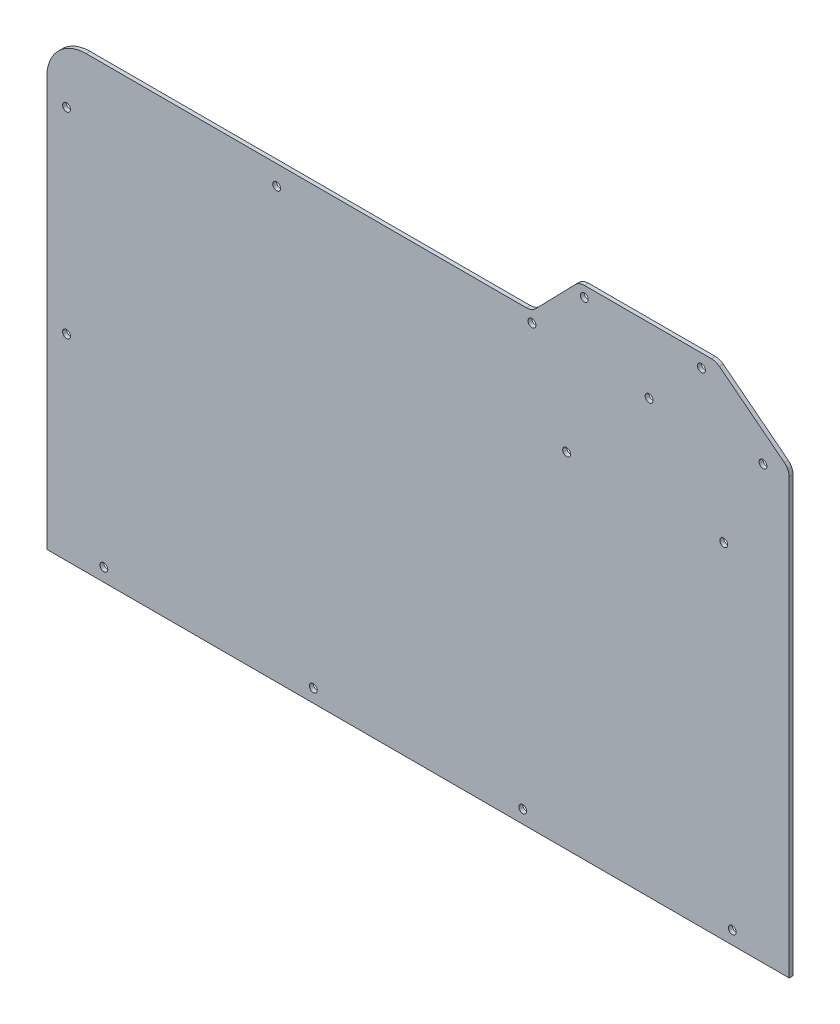
SolidWorks part; units mm, degrees
material "Alliage 1060"
ref_plane "Plan de face" through (0, 0, 0) normal (0, 0, 1) x (1, 0, 0)
ref_plane "Plan de dessus" through (0, 0, 0) normal (0, 1, 0) x (1, 0, 0)
ref_plane "Plan de droite" through (0, 0, 0) normal (1, 0, 0) x (0, 0, -1)
sketch "Esquisse1" plane through (0, 0, 0) normal (0, 0, 1) x (1, 0, 0)
  line L0 (185.25, 171.5) -> (203.25, 190)
  line L1 (0, 0) -> (283.5, 0)
  line L2 (0, 0) -> (0, 171.5)
  line L3 (0, 171.5) -> (185.25, 171.5)
  line L4 (283.5, 0) -> (283.5, 168.124)
  line L5 (203.25, 190) -> (255.5, 190)
  line L6 (255.5, 190) -> (283.5, 168.124)
  line L7 (15, 171.5) -> (180, 171.5) construction
  line L8 (201.7777, 188.4868) -> (186.7223, 173.0132) construction
  line L9 (253.7784, 190) -> (208.5, 190) construction
  line L10 (281.5783, 169.6254) -> (256.8567, 188.9401) construction
  line L11 (283.5, 165) -> (283.5, 0) construction
extrude "Boss.-Extru.1" add sketch "Esquisse1" along normal blind 1.5
sketch "Esquisse2" plane through (0, 0, 1.5) normal (0, 0, 1) x (1, 0, 0)
  circle A0 centre (261.75, 5) radius 1.5
  circle A1 centre (181.75, 5) radius 1.5
  circle A2 centre (101.75, 5) radius 1.5
  circle A3 centre (21.75, 5) radius 1.5
  circle A4 centre (7.5, 75) radius 1.5
  circle A5 centre (7.5, 150) radius 1.5
  circle A6 centre (87.75, 164) radius 1.5
  circle A7 centre (185.25, 167.5) radius 1.5
  circle A8 centre (205.25, 186) radius 1.5
  circle A9 centre (230, 165) radius 1.5
  circle A10 centre (250, 185) radius 1.5
  circle A11 centre (273.5, 165) radius 1.5
  circle A12 centre (261.75, 5) radius 1.2 construction
  circle A13 centre (181.75, 5) radius 1.2 construction
  circle A14 centre (101.75, 5) radius 1.2 construction
  circle A15 centre (21.75, 5) radius 1.2 construction
  circle A16 centre (7.5, 75) radius 1.2 construction
  circle A17 centre (7.5, 150) radius 1.2 construction
  circle A18 centre (87.75, 164) radius 1.2 construction
  circle A19 centre (185.25, 167.5) radius 1.2 construction
  circle A20 centre (205.25, 186) radius 1.2 construction
  circle A21 centre (230, 165) radius 1.25 construction
  circle A22 centre (250, 185) radius 1.25 construction
  circle A23 centre (273.5, 165) radius 1.2 construction
  dimension "D1" = 3
extrude "Enlèv. mat.-Extru.1" cut sketch "Esquisse2" against normal through all
fillet "Congé1" radius 5 4 edges at (283.5, 168.124, 0.75) (255.5, 190, 0.75) (203.25, 190, 0.75) (185.25, 171.5, 0.75)
fillet "Congé2" radius 15 1 edges at (0, 171.5, 0.75)
sketch "Esquisse3" plane through (0, 0, 1.5) normal (0, 0, 1) x (1, 0, 0)
  line L0 (283.5, 0) -> (283.5, 165.6853) construction
  line L1 (183.1387, 171.5) -> (15, 171.5) construction
  circle A0 centre (198.5, 131.5) radius 1.5
  circle A1 centre (258.5, 131.5) radius 1.5
  dimension "D1" = 60
  dimension "D2" = 3
  dimension "D3" = 25
  dimension "D4" = 40
extrude "Enlèv. mat.-Extru.2" cut sketch "Esquisse3" against normal through all
